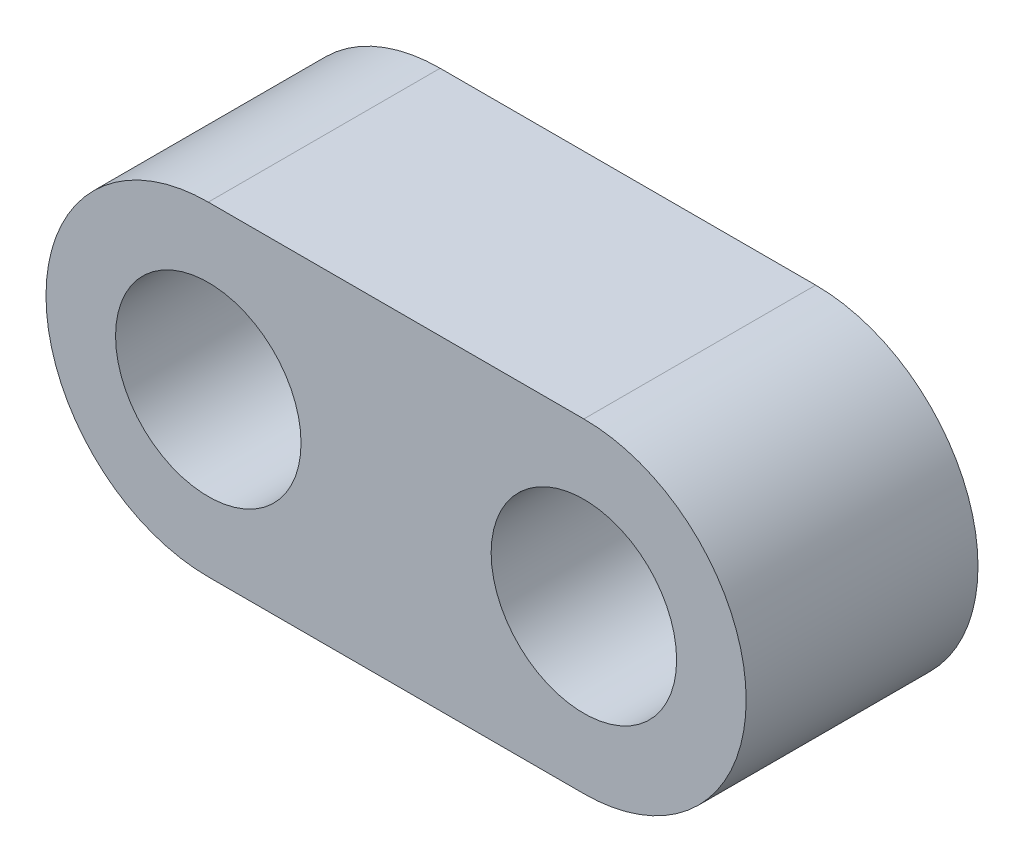
SolidWorks part; units mm, degrees
ref_plane "前视基准面" through (0, 0, 0) normal (0, 0, 1) x (1, 0, 0)
ref_plane "上视基准面" through (0, 0, 0) normal (0, 1, 0) x (1, 0, 0)
ref_plane "右视基准面" through (0, 0, 0) normal (1, 0, 0) x (0, 0, -1)
other "Configuration Table"
sketch "草图2" plane through (0, 0, 0) normal (0, 0, 1) x (1, 0, 0)
  line L0 (0, 0) -> (81, 0)
  line L1 (0, 35) -> (81, 35)
  line L3 (81, -35) -> (0, -35)
  arc A0 (0, 35) -> (0, -35) centre (0, 0) ccw
  arc A1 (81, -35) -> (81, 35) centre (81, 0) ccw
  circle A2 centre (0, 0) radius 20
  circle A3 centre (81, 0) radius 20
  dimension "D1" = 35
  dimension "D2" = 40
  dimension "D3" = 81
extrude "凸台-拉伸1" add sketch "草图2" along normal blind 50
